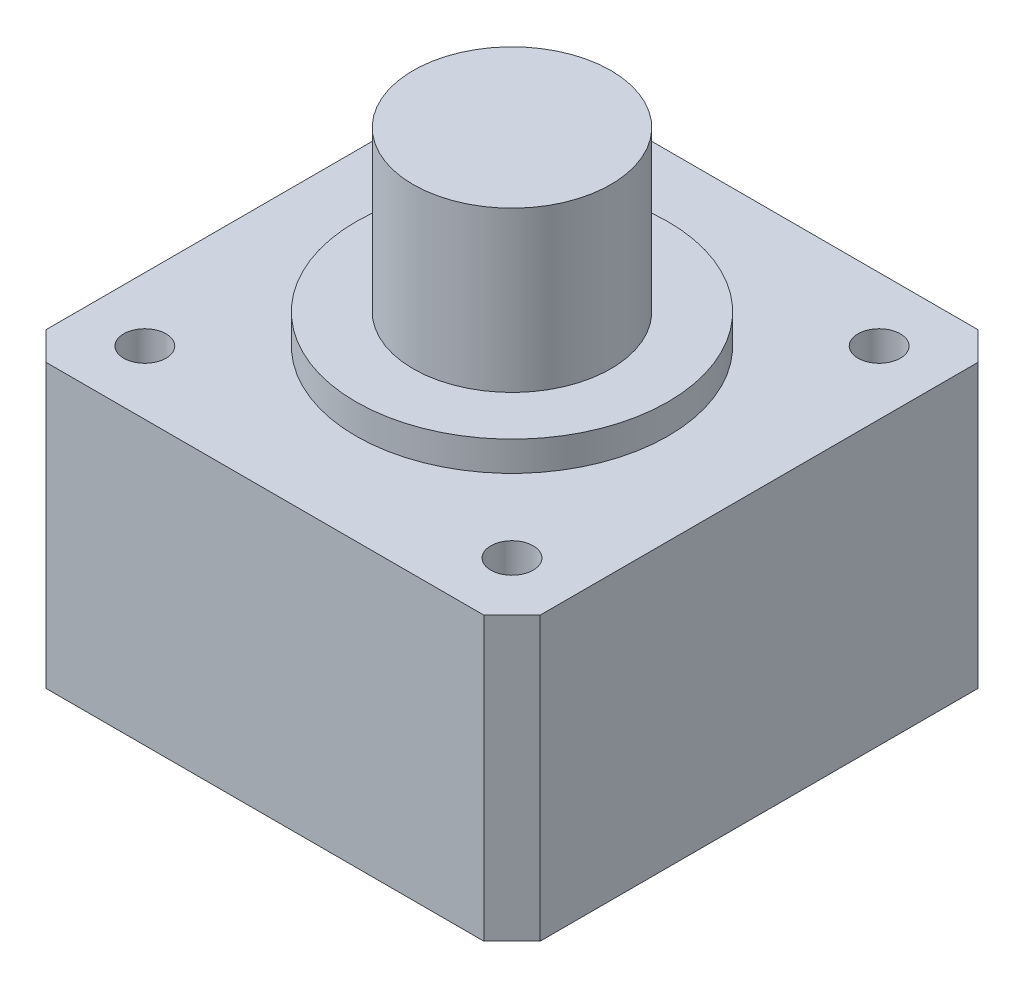
SolidWorks part; units mm, degrees
ref_plane "Front Plane" through (0, 0, 0) normal (0, 0, 1) x (1, 0, 0)
ref_plane "Top Plane" through (0, 0, 0) normal (0, 1, 0) x (1, 0, 0)
ref_plane "Right Plane" through (0, 0, 0) normal (1, 0, 0) x (0, 0, -1)
sketch "Sketch1" plane through (0, 0, 0) normal (0, 1, 0) x (1, 0, 0)
  line L1 (-17.5, 17.5) -> (17.5, 17.5)
  line L2 (-17.5, 17.5) -> (-17.5, -17.5)
  line L3 (-17.5, -17.5) -> (17.5, -17.5)
  line L4 (17.5, 17.5) -> (17.5, -17.5)
  line L5 (-17.5, 17.5) -> (17.5, -17.5) construction
  line L6 (-17.5, -17.5) -> (17.5, 17.5) construction
  point P0 (0, 0)
extrude "Boss-Extrude1" add sketch "Sketch1" along normal blind 20
sketch "Sketch2" plane through (0, 20, 0) normal (0, 1, 0) x (1, 0, 0)
  circle A0 centre (0, 0) radius 2.5
sketch "Sketch3" plane through (0, 20, 0) normal (0, 1, 0) x (1, 0, 0)
  line L1 (-13, 13) -> (13, 13)
  line L2 (-13, 13) -> (-13, -13)
  line L3 (-13, -13) -> (13, -13)
  line L4 (13, 13) -> (13, -13)
  line L5 (-13, 13) -> (13, -13) construction
  line L6 (-13, -13) -> (13, 13) construction
  circle A0 centre (13, 13) radius 1.5
  circle A1 centre (13, -13) radius 1.5
  circle A2 centre (-13, -13) radius 1.5
  circle A3 centre (-13, 13) radius 1.5
  point P0 (0, 0)
extrude "Cut-Extrude1" cut sketch "Sketch3" against normal blind 20 contours A3 | A0 | A1 | A2
chamfer "Chamfer1" distance 2 angle 45 4 edges at (-17.5, 10, 17.5) (-17.5, 10, -17.5) (17.5, 10, -17.5) (17.5, 10, 17.5)
sketch "Sketch4" plane through (0, 20, 0) normal (0, 1, 0) x (1, 0, 0)
  circle A0 centre (0, 0) radius 11.05
extrude "Boss-Extrude2" add sketch "Sketch4" along normal blind 2.1
sketch "Sketch5" plane through (0, 22.1, 0) normal (0, 1, 0) x (1, 0, 0)
  circle A0 centre (0, 0) radius 7
extrude "Boss-Extrude3" add sketch "Sketch5" along normal blind 11.3
